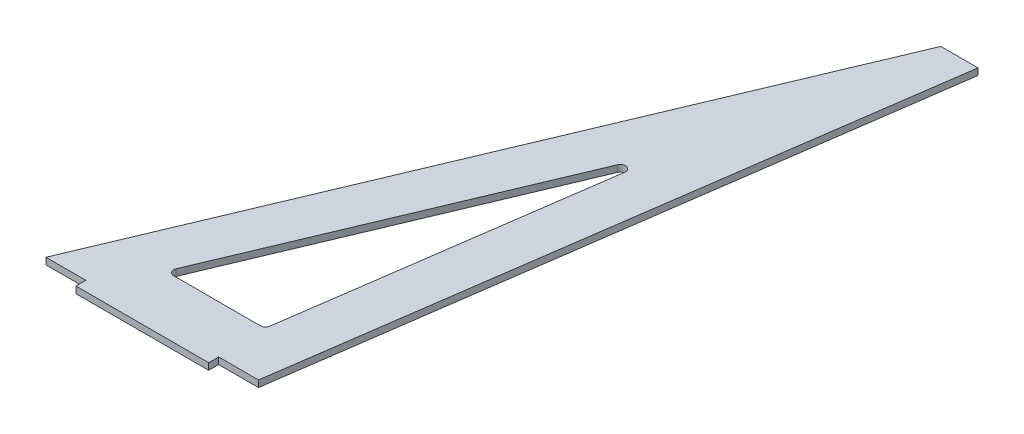
SolidWorks part; units mm, degrees
material "Balsa"
ref_plane "Front Plane" through (0, 0, 0) normal (0, 0, 1) x (1, 0, 0)
ref_plane "Top Plane" through (0, 0, 0) normal (0, 1, 0) x (1, 0, 0)
ref_plane "Right Plane" through (0, 0, 0) normal (1, 0, 0) x (0, 0, -1)
sketch "Sketch1" plane through (0, 0, 0) normal (0, 1, 0) x (1, 0, 0)
  line L0 (0, 0) -> (2.336, 0) construction
  line L1 (0, 0) -> (0, -1.1) construction
  line L2 (0, 301.244) -> (-42.7949, 0)
  line L3 (-42.7949, 0) -> (-144.3949, 0)
  line L4 (-144.3949, 0) -> (-17.78, 301.244)
  line L5 (-17.78, 301.244) -> (0, 301.244)
  dimension "D1" = 17.78
  dimension "D2" = 101.6
  dimension "D3" = 326.771
  dimension "D4" = 301.244
extrude "Boss-Extrude1" add sketch "Sketch1" along normal blind 3.175
sketch "Sketch2" plane through (0, 3.175, 0) normal (0, 1, 0) x (1, 0, 0)
  line L8 (-38.4607, 193.0425) -> (-109.9896, 22.86)
  line L9 (-109.9896, 22.86) -> (-62.6369, 22.86)
  line L10 (-62.6369, 22.86) -> (-38.4607, 193.0425)
  line L11 (-38.4607, 193.0425) -> (-109.9896, 22.86)
  line L12 (-109.9896, 22.86) -> (-62.6369, 22.86)
  line L13 (-62.6369, 22.86) -> (-38.4607, 193.0425)
  dimension "D1" = 22.86
extrude "Cut-Extrude1" cut sketch "Sketch2" against normal up to next
fillet "Fillet1" radius 2.54 3 edges at (-38.4607, 1.5875, -193.0425) (-109.9896, 1.5875, -22.86) (-62.6369, 1.5875, -22.86)
sketch "Sketch3" plane through (0, 0, 0) normal (0, 0, 1) x (1, 0, 0)
  line L0 (-93.5949, 3.175) -> (-93.5949, 0) construction
  line L1 (-144.3949, 3.175) -> (-42.7949, 3.175) construction
  line L2 (-144.3949, 0) -> (-42.7949, 0) construction
  line L4 (-125.3449, 3.175) -> (-61.8449, 3.175)
  line L5 (-125.3449, 3.175) -> (-125.3449, 0)
  line L6 (-125.3449, 0) -> (-61.8449, 0)
  line L7 (-61.8449, 3.175) -> (-61.8449, 0)
  line L8 (-125.3449, 3.175) -> (-61.8449, 0) construction
  line L9 (-125.3449, 0) -> (-61.8449, 3.175) construction
  point P6 (-93.5949, 1.5875)
  dimension "D1" = 63.5
extrude "Boss-Extrude2" add sketch "Sketch3" along normal blind 4.7625
